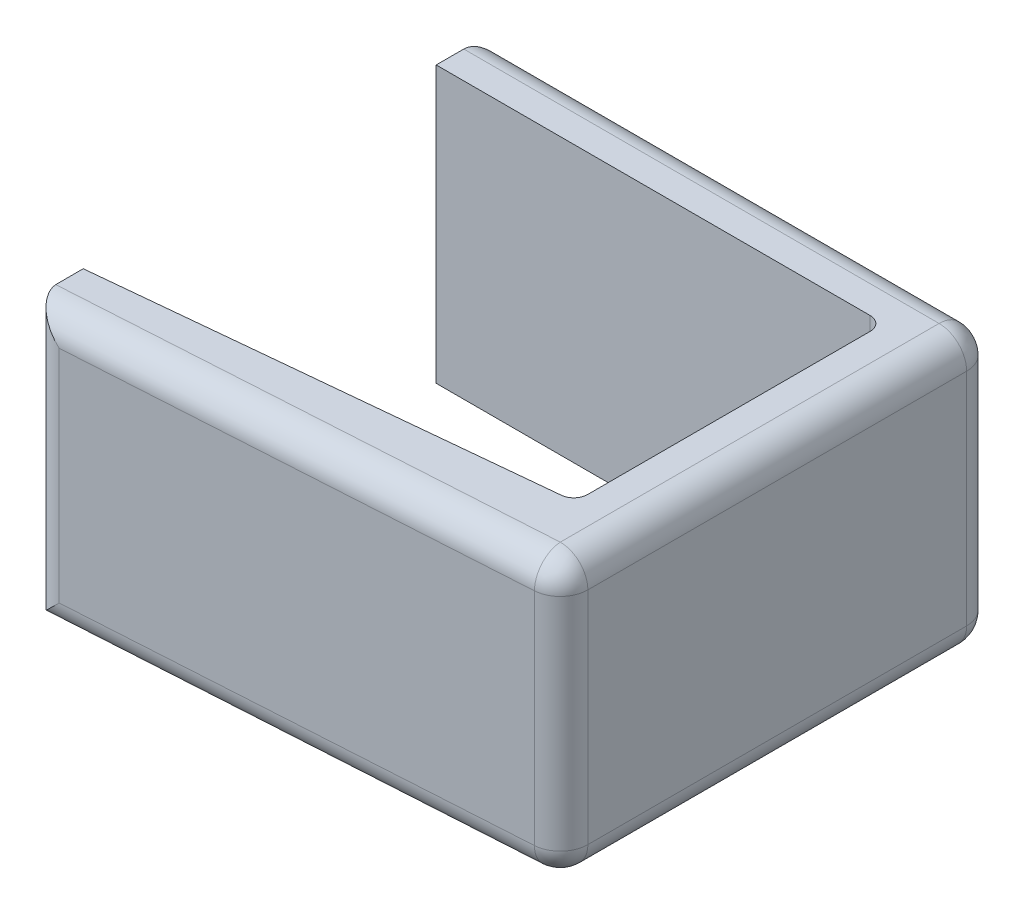
SolidWorks part; units mm, degrees
ref_plane "Front Plane" through (0, 0, 0) normal (0, 0, 1) x (1, 0, 0)
ref_plane "Top Plane" through (0, 0, 0) normal (0, 1, 0) x (1, 0, 0)
ref_plane "Right Plane" through (0, 0, 0) normal (1, 0, 0) x (0, 0, -1)
sketch "Sketch1" plane through (0, 0, 0) normal (0, 1, 0) x (1, 0, 0)
  line L1 (-8.1186, -7.9) -> (8.1186, -7.9)
  line L3 (-8.1186, 7.9) -> (8.1186, 7.9)
  line L4 (8.1186, -7.9) -> (8.1186, 7.9)
  line L5 (-8.1186, -7.9) -> (8.1186, 7.9) construction
  line L6 (-8.1186, 7.9) -> (8.1186, -7.9) construction
  line L7 (-8.1186, 9.9) -> (10.1186, 9.9)
  line L8 (10.1186, -9.9) -> (10.1186, 9.9)
  line L9 (-8.1186, -9.9) -> (10.1186, -9.9)
  line L10 (-8.1186, 7.9) -> (-8.1186, 9.9)
  line L11 (-8.1186, 9.9) -> (-8.1186, 7.9)
  line L12 (-10.1186, 9.9) -> (10.1186, 9.9) construction
  line L13 (-10.1186, -9.9) -> (-10.1186, 9.9) construction
  line L14 (-10.1186, -9.9) -> (10.1186, -9.9) construction
  line L15 (-8.1186, -7.9) -> (-8.1186, 7.9) construction
  line L16 (-8.1186, -7.9) -> (-8.1186, -9.9)
  line L17 (8.1186, -7.9) -> (8.1186, -3.3)
  line L18 (-8.1186, -7.9) -> (-8.1186, -4.9)
  line L19 (-8.1186, -4.9) -> (8.1186, -3.3)
  line L20 (-8.1186, -4.9) -> (-8.1186, -6.9)
  line L21 (-8.1186, -6.9) -> (8.1186, -5.9)
  line L22 (5.1156, -6.0849) -> (10.1186, -5.7768)
  point P0 (0, 0)
  dimension "D1" = 15.8
  dimension "D3" = 4.6
  dimension "D4" = 2
  dimension "D2" = 2
extrude "Boss-Extrude1" add sketch "Sketch1" along normal blind 10 contours L1 L16 L9 L8 L7 L10 L3 L4 | L18 L21 L17 L19
fillet "Fillet1" radius 1 10 edges at (1, 10, -9.9) (-8.1186, 5, -9.9) (1, 0, -9.9) (10.1186, 10, -2.0616) (10.1186, 5, -9.9) (10.1186, 0, -2.0616) (10.1186, 5, 5.7768) (-8.1186, 5, 6.9) (1, 10, 6.3384) (1, 0, 6.3384)
fillet "Fillet2" radius 0.5 2 edges at (8.1186, 5, -7.9) (8.1186, 5, 3.3)
